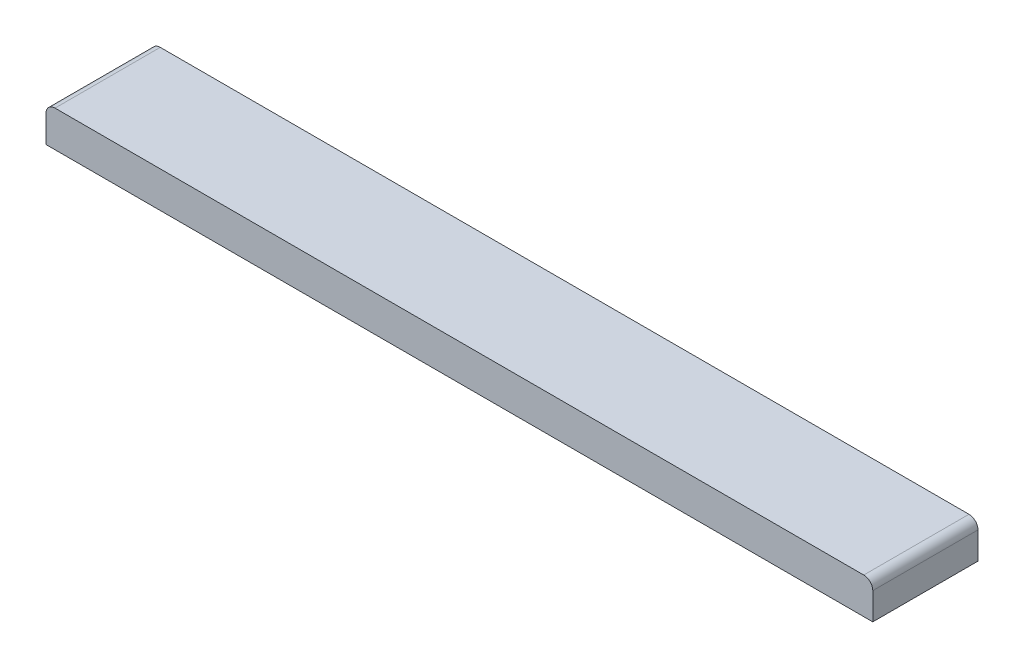
SolidWorks part; units mm, degrees
ref_plane "前视基准面" through (0, 0, 0) normal (0, 0, 1) x (1, 0, 0)
ref_plane "上视基准面" through (0, 0, 0) normal (0, 1, 0) x (1, 0, 0)
ref_plane "右视基准面" through (0, 0, 0) normal (1, 0, 0) x (0, 0, -1)
sketch "草图1" plane through (0, 0, 0) normal (0, 1, 0) x (1, 0, 0)
  line L1 (-137.5, -17.5) -> (137.5, -17.5)
  line L2 (-137.5, -17.5) -> (-137.5, 17.5)
  line L3 (-137.5, 17.5) -> (137.5, 17.5)
  line L4 (137.5, -17.5) -> (137.5, 17.5)
  line L5 (-137.5, -17.5) -> (137.5, 17.5) construction
  line L6 (-137.5, 17.5) -> (137.5, -17.5) construction
  point P0 (0, 0)
  dimension "D1" = 275
  dimension "D2" = 35
extrude "凸台-拉伸1" add sketch "草图1" along normal blind 12
fillet "圆角1" radius 3 2 edges at (137.5, 12, 0) (-137.5, 12, 0)
